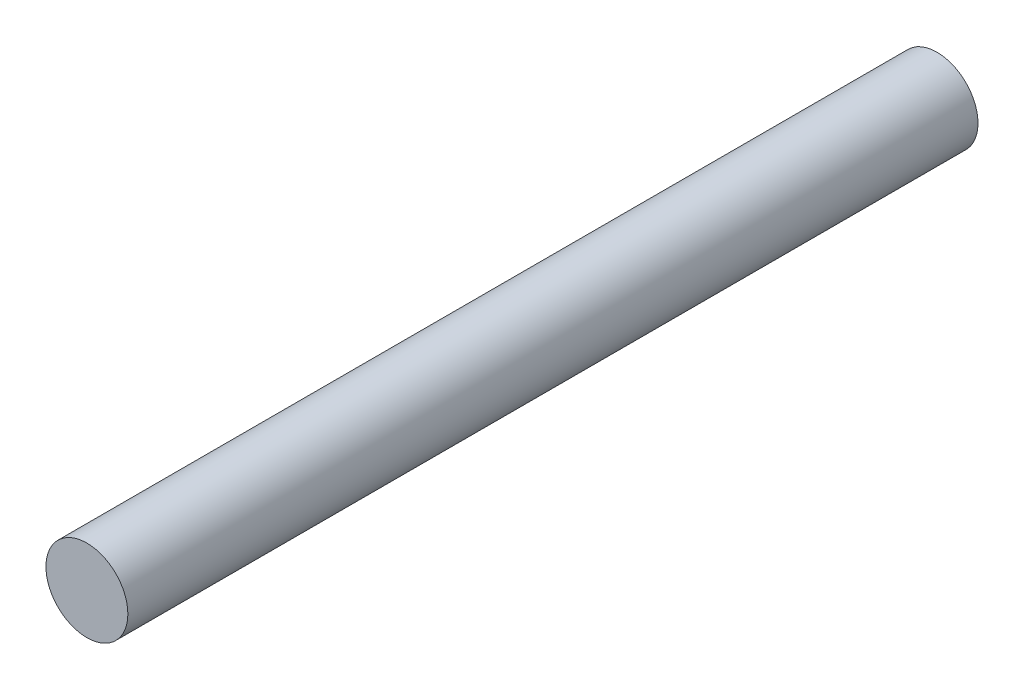
SolidWorks part; units mm, degrees
material "Thornel Mat VMA"
ref_plane "Front Plane" through (0, 0, 0) normal (0, 0, 1) x (1, 0, 0)
ref_plane "Top Plane" through (0, 0, 0) normal (0, 1, 0) x (1, 0, 0)
ref_plane "Right Plane" through (0, 0, 0) normal (1, 0, 0) x (0, 0, -1)
sketch "Sketch1" plane through (0, 0, 0) normal (0, 0, 1) x (1, 0, 0)
  circle A0 centre (0, 0) radius 2
  dimension "D1" = 4
extrude "Boss-Extrude1" add sketch "Sketch1" along normal blind 41.5
